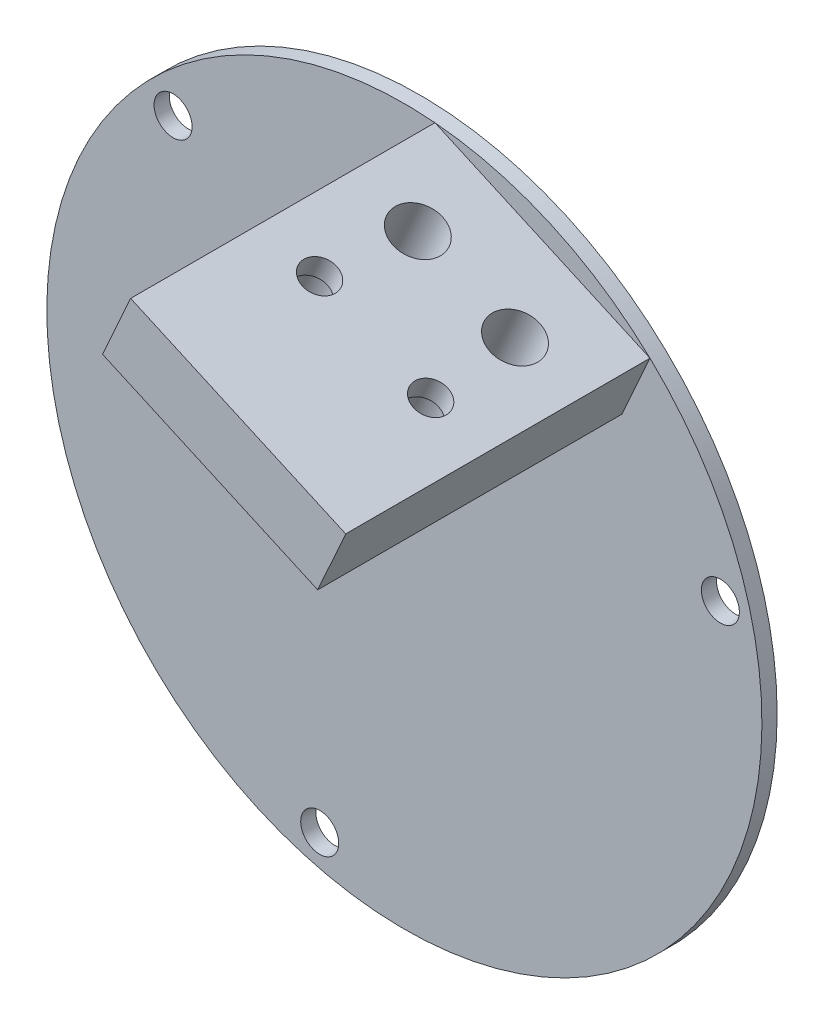
SolidWorks part; units mm, degrees
ref_plane "Plan de face" through (0, 0, 0) normal (0, 0, 1) x (1, 0, 0)
ref_plane "Plan de dessus" through (0, 0, 0) normal (0, 1, 0) x (1, 0, 0)
ref_plane "Plan de droite" through (0, 0, 0) normal (1, 0, 0) x (0, 0, -1)
sketch "Sketch1" plane through (0, 0, 0) normal (0, 0, 1) x (1, 0, 0)
  circle A0 centre (0, 0) radius 47
  dimension "D1" = 94
extrude "Boss-Extrude1" add sketch "Sketch1" along normal blind 2
sketch "Sketch3" plane through (0, 0, 0) normal (0, 0, -1) x (-1, 0, 0)
  line L0 (0, 0) -> (0, 43) construction
  line L1 (0, 0) -> (30.4056, 30.4056) construction
  circle A0 centre (0, 0) radius 43 construction
  circle A1 centre (30.4056, 30.4056) radius 2.5
  circle A2 centre (11.1292, -41.5348) radius 2.5
  circle A3 centre (-41.5348, 11.1292) radius 2.5
  point P13 (0, 0)
  dimension "D1" = 86
  dimension "D2" = 5
  dimension "D3" = 45
  dimension "D4" = 3
extrude "Cut-Extrude1" cut sketch "Sketch3" against normal through all contours A3 | A1 | A2
sketch "Sketch4" plane through (0, 0, 2) normal (0, 0, 1) x (1, 0, 0)
  line L0 (-22.2135, -49.5439) -> (25.9538, 57.8861) construction
  line L3 (-30.4056, 30.4056) -> (42.9287, -2.4745) construction
  line L6 (4.021, 46.8277) -> (32.2879, 34.1539)
  line L7 (32.2879, 34.1539) -> (28.6058, 25.9416)
  line L8 (28.6058, 25.9416) -> (0.3389, 38.6154)
  line L9 (0.3389, 38.6154) -> (4.021, 46.8277)
  circle A2 centre (-30.4056, 30.4056) radius 2.5 construction
  circle A3 centre (0, 0) radius 47 construction
  circle A6 centre (-30.4056, 30.4056) radius 2.5 construction
  circle A7 centre (0, 0) radius 47 construction
  circle A8 centre (-30.4056, 30.4056) radius 4.25 construction
  circle A9 centre (42.9287, -2.4745) radius 2.5 construction
  circle A10 centre (42.9287, -2.4745) radius 4.25 construction
  circle A11 centre (-22.2135, -49.5439) radius 2.5 construction
  circle A12 centre (-22.2135, -49.5439) radius 4.25 construction
  point P16 (-3.2301, -7.2043)
  point P18 (14.444, 32.2151)
  point P19 (18.1544, 40.4908)
  dimension "D1" = 8.5
  dimension "D3" = 9
  dimension "D2" = 3
extrude "Boss-Extrude2" add sketch "Sketch4" along normal blind 40
sketch "Sketch8" plane through (18.1544, 40.4908, 0) normal (0.4091, 0.9125, 0) x (0.9125, -0.4091, 0)
  line L0 (0, -2) -> (0, -42) construction
  line L3 (15.489, -2) -> (-15.489, -2) construction
  line L4 (15.489, -42) -> (-15.489, -42) construction
  line L5 (-7, -12) -> (7, -12) construction
  line L6 (0, -24) -> (8, -24) construction
  circle A0 centre (7, -12) radius 3.25
  circle A3 centre (-7, -12) radius 3.25
  circle A4 centre (8, -24) radius 2.25
  circle A5 centre (-8, -24) radius 2.25
  point P9 (0, -12)
  point P12 (0, -24)
  point P16 (6, -24)
  dimension "D3" = 6.5
  dimension "D4" = 4.5
  dimension "D1" = 7
  dimension "D2" = 8
  dimension "D6" = 12
  dimension "D7" = 10
extrude "Cut-Extrude3" cut sketch "Sketch8" against normal up to next
sketch "Sketch9" plane through (14.4724, 32.2785, 0) normal (-0.4091, -0.9125, 0) x (0.9125, -0.4091, 0)
  line L0 (0, 2) -> (0, 42) construction
  line L1 (47, 2) -> (-47, 2) construction
  line L2 (-15.489, 42) -> (15.489, 42) construction
  line L3 (-1.5, 18.5) -> (-12.5, 18.5)
  line L4 (1.5, 5.5) -> (12.5, 5.5)
  line L5 (1.5, 5.5) -> (1.5, 18.5)
  line L6 (1.5, 18.5) -> (12.5, 18.5)
  line L7 (12.5, 5.5) -> (12.5, 18.5)
  line L8 (1.5, 5.5) -> (12.5, 18.5) construction
  line L9 (1.5, 18.5) -> (12.5, 5.5) construction
  line L10 (-12.5, 5.5) -> (-12.5, 18.5)
  line L11 (-1.5, 5.5) -> (-12.5, 5.5)
  line L12 (-1.5, 5.5) -> (-1.5, 18.5)
  circle A1 centre (7, 12) radius 3.25 construction
  circle A3 centre (7, 12) radius 3.25 construction
  dimension "D1" = 13
  dimension "D2" = 11
extrude "Cut-Extrude4" cut sketch "Sketch9" against normal blind 1
sketch "Sketch10" plane through (14.4724, 32.2785, 0) normal (-0.4091, -0.9125, 0) x (0.9125, -0.4091, 0)
  line L0 (0, 2) -> (0, 42) construction
  line L1 (-15.489, 2) -> (15.489, 2) construction
  line L2 (-15.489, 42) -> (15.489, 42) construction
  line L3 (-8, 24) -> (8, 24) construction
  line L4 (5.25, 25.8767) -> (5.25, 22.1233) construction
  line L5 (5.25, 25.199) -> (5.25, 22.801)
  line L6 (-5.25, 25.199) -> (-5.25, 22.801)
  circle A1 centre (8, 24) radius 2.25 construction
  circle A4 centre (8, 24) radius 2.25 construction
  arc A6 (5.25, 25.199) -> (5.25, 22.801) centre (8, 24) cw
  arc A7 (-5.25, 25.199) -> (-5.25, 22.801) centre (-8, 24) ccw
  point P12 (0, 24)
  point P14 (5.25, 24)
  dimension "D1" = 2.75
  dimension "D2" = 3
extrude "Cut-Extrude5" cut sketch "Sketch10" against normal blind 6
